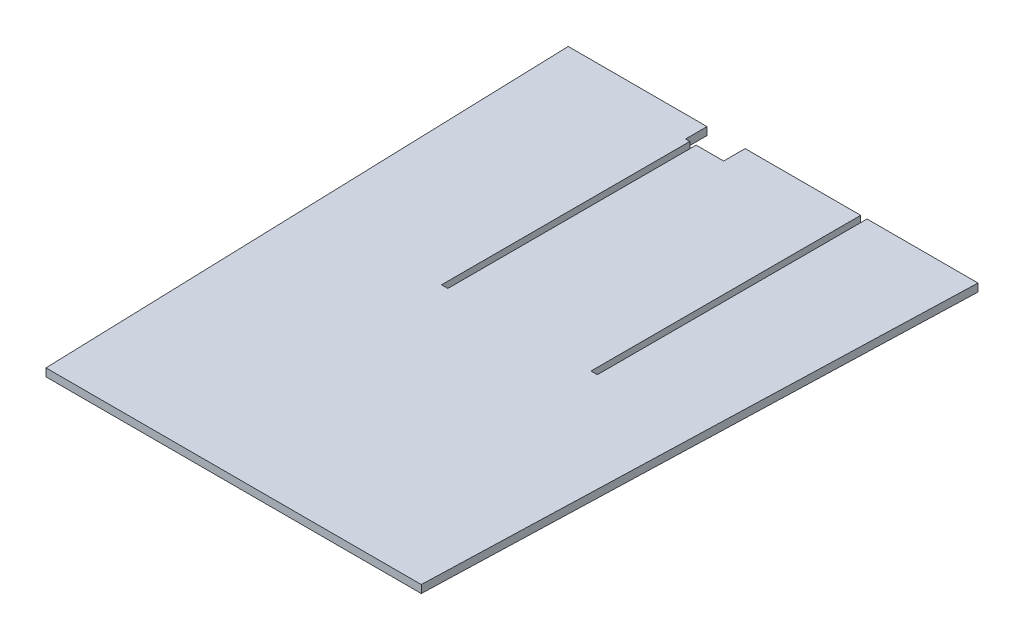
SolidWorks part; units mm, degrees
ref_plane "Front Plane" through (0, 0, 0) normal (0, 0, 1) x (1, 0, 0)
ref_plane "Top Plane" through (0, 0, 0) normal (0, 1, 0) x (1, 0, 0)
ref_plane "Right Plane" through (0, 0, 0) normal (1, 0, 0) x (0, 0, -1)
sketch "Sketch1" plane through (0, 0, 0) normal (0, 1, 0) x (1, 0, 0)
  line L14 (198.5799, 458.6378) -> (311.3305, 458.6378)
  line L15 (212.5905, 20.4878) -> (517.3905, 20.4878)
  line L16 (198.5799, 458.6378) -> (212.5905, 20.4878)
  line L17 (531.4011, 458.6378) -> (517.3905, 20.4878)
  line L20 (311.3305, 458.6378) -> (311.3305, 441.1753)
  line L21 (342.2804, 458.6378) -> (342.2804, 441.1753)
  line L22 (342.2804, 441.1753) -> (319.9427, 441.1753)
  line L23 (314.7833, 441.1753) -> (314.7833, 239.5628)
  line L24 (319.9427, 441.1753) -> (319.9427, 239.5628)
  line L25 (314.7833, 239.5628) -> (319.9427, 239.5628)
  line L26 (342.2804, 458.6378) -> (436.1461, 458.6378)
  line L27 (314.7833, 441.1753) -> (311.3305, 441.1753)
  line L28 (436.1461, 458.6378) -> (436.1461, 239.5628)
  line L29 (441.3055, 458.6378) -> (441.3055, 239.5628)
  line L30 (436.1461, 239.5628) -> (441.3055, 239.5628)
  line L31 (441.3055, 458.6378) -> (531.4011, 458.6378)
extrude "Boss-Extrude1" add sketch "Sketch1" along normal blind 6.35 contours L16 L15 L17 L31 L29 L30 L28 L26 L21 L22 L24 L25 L23 L27 L20 L14
